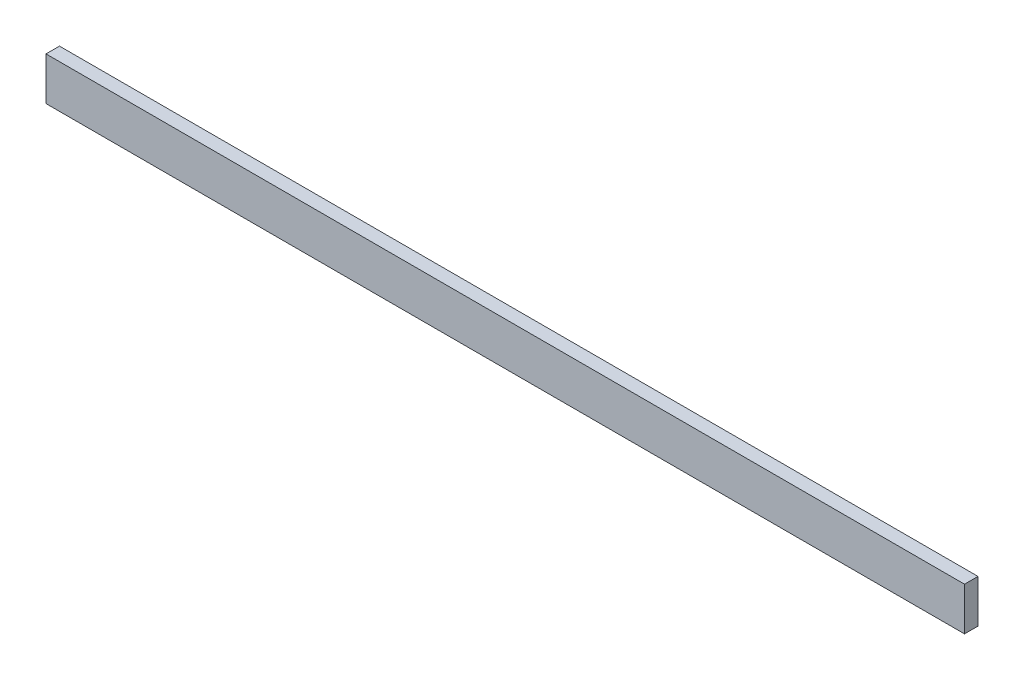
SolidWorks part; units mm, degrees
ref_plane "Front Plane" through (0, 0, 0) normal (0, 0, 1) x (1, 0, 0)
ref_plane "Top Plane" through (0, 0, 0) normal (0, 1, 0) x (1, 0, 0)
ref_plane "Right Plane" through (0, 0, 0) normal (1, 0, 0) x (0, 0, -1)
sketch "Sketch1" plane through (0, 0, 0) normal (1, 0, 0) x (0, 0, -1)
  line L1 (23.5, -75) -> (-23.5, -75)
  line L2 (23.5, -75) -> (23.5, 75)
  line L3 (23.5, 75) -> (-23.5, 75)
  line L4 (-23.5, -75) -> (-23.5, 75)
  line L5 (23.5, -75) -> (-23.5, 75) construction
  line L6 (23.5, 75) -> (-23.5, -75) construction
  point P0 (0, 0)
  dimension "D1" = 47
  dimension "D2" = 150
extrude "Boss-Extrude1" add sketch "Sketch1" along normal blind 3200
